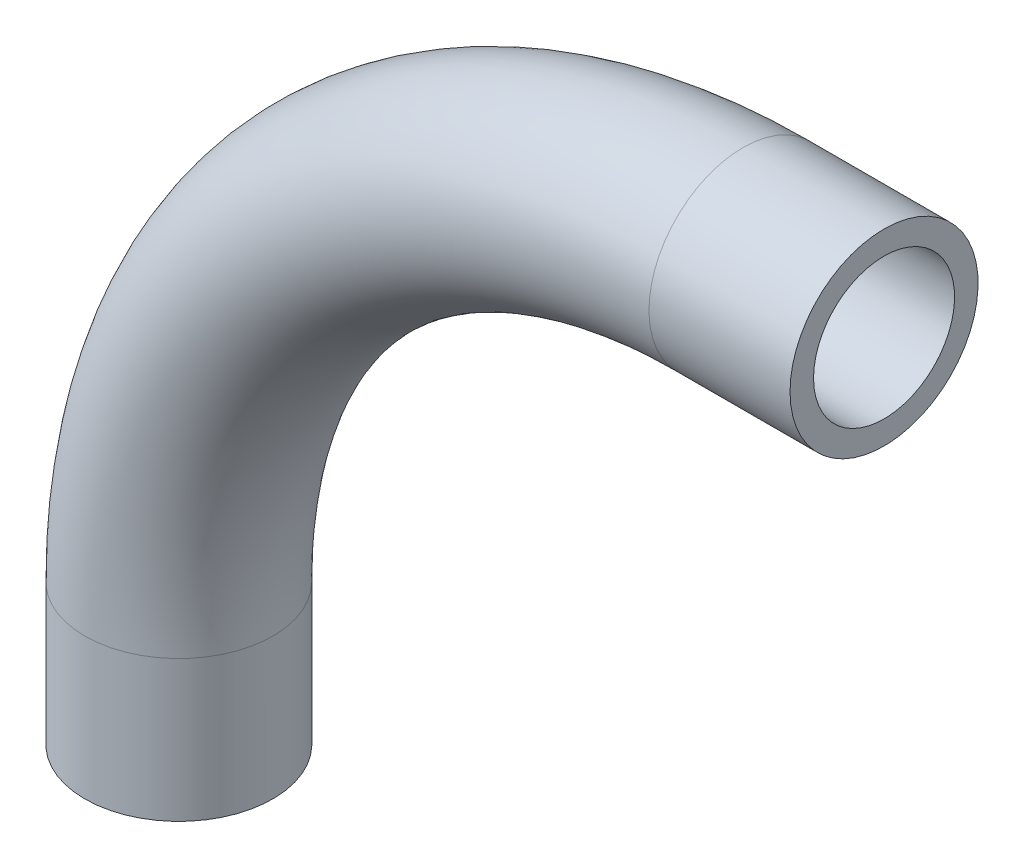
SolidWorks part; units mm, degrees
ref_plane "Front Plane" through (0, 0, 0) normal (0, 0, 1) x (1, 0, 0)
ref_plane "Top Plane" through (0, 0, 0) normal (0, 1, 0) x (1, 0, 0)
ref_plane "Right Plane" through (0, 0, 0) normal (1, 0, 0) x (0, 0, -1)
sketch "Sketch1" plane through (0, 0, 0) normal (0, 0, 1) x (1, 0, 0)
  line L0 (0, 0) -> (0, 6)
  line L1 (24, 30) -> (30, 30)
  arc A0 (0, 6) -> (24, 30) centre (24, 6) cw
  point P6 (0, 30)
  dimension "D3" = 24
  dimension "D1" = 30
  dimension "D2" = 30
  dimension "D4" = 90
sketch "Sketch2" plane through (0, 0, 0) normal (0, 1, 0) x (1, 0, 0)
  circle A0 centre (0, 0) radius 4
  circle A1 centre (0, 0) radius 3
  dimension "D1" = 6
  dimension "D2" = 8
sweep "Sweep1" add profiles "Sketch2" path "Sketch1"
